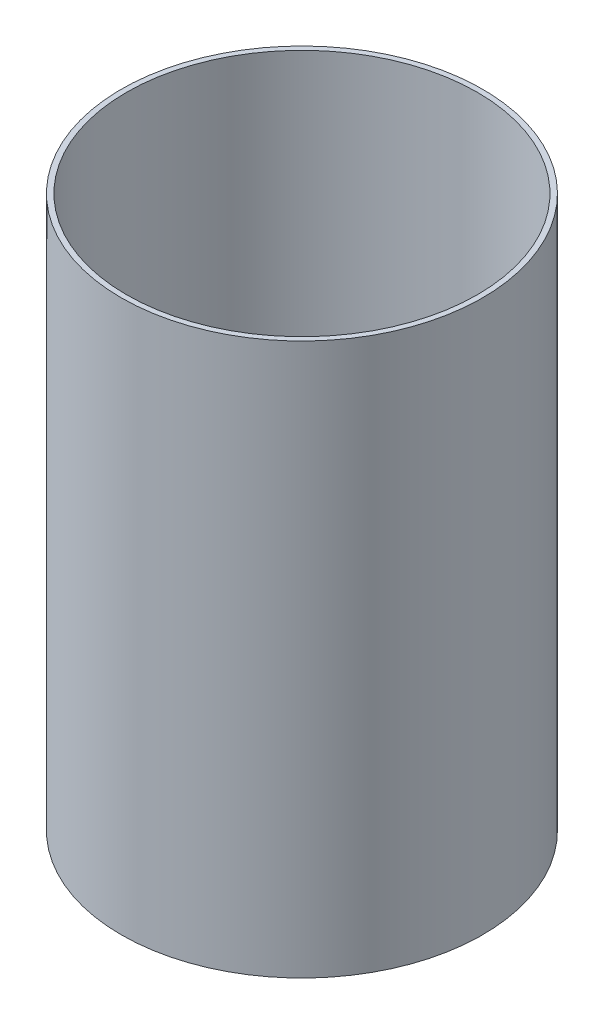
SolidWorks part; units mm, degrees
ref_plane "Front Plane" through (0, 0, 0) normal (0, 0, 1) x (1, 0, 0)
ref_plane "Top Plane" through (0, 0, 0) normal (0, 1, 0) x (1, 0, 0)
ref_plane "Right Plane" through (0, 0, 0) normal (1, 0, 0) x (0, 0, -1)
sketch "Sketch1" plane through (0, 0, 0) normal (0, 1, 0) x (1, 0, 0)
  circle A0 centre (0, 0) radius 38.15
  circle A1 centre (0, 0) radius 39.3
  dimension "D1" = 78.6
  dimension "D2" = 76.3
extrude "Boss-Extrude1" add sketch "Sketch1" along normal blind 120
ref_plane "Plane1" through (-27.7893, 0, -27.7893) normal (-0.7071, 0, -0.7071) x (0, -1, 0)
